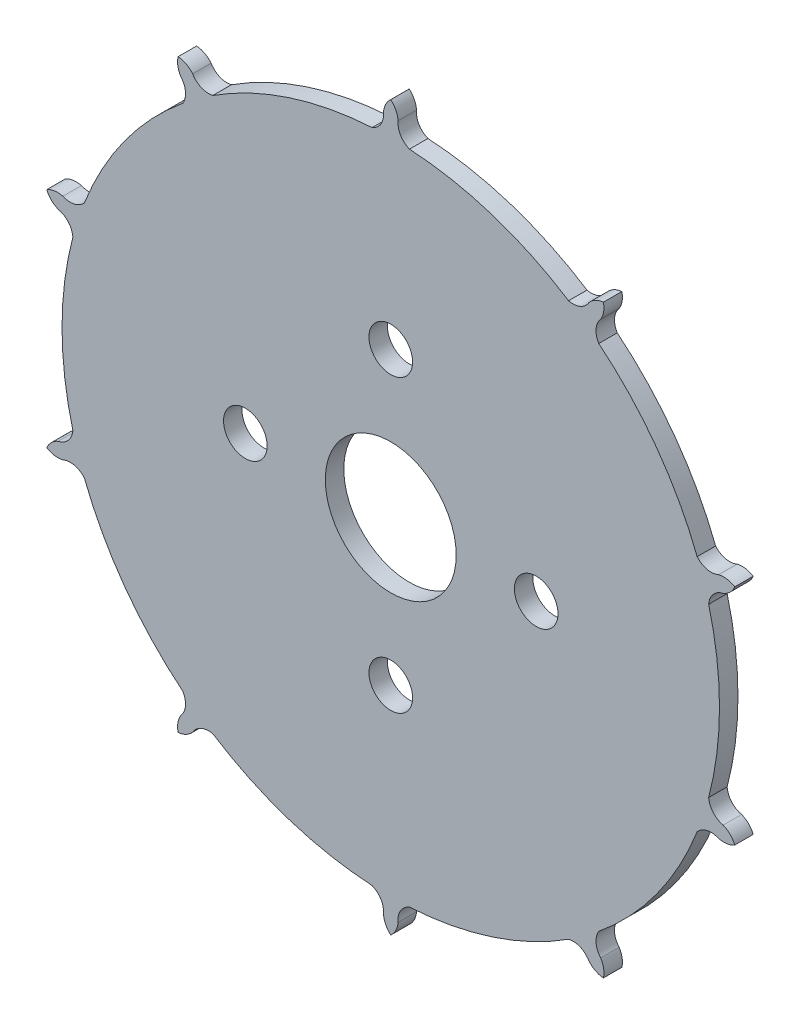
SolidWorks part; units mm, degrees
ref_plane "Front Plane" through (0, 0, 0) normal (0, 0, 1) x (1, 0, 0)
ref_plane "Top Plane" through (0, 0, 0) normal (0, 1, 0) x (1, 0, 0)
ref_plane "Right Plane" through (0, 0, 0) normal (1, 0, 0) x (0, 0, -1)
sketch "Sketch1" plane through (0, 0, 0) normal (0, 0, 1) x (1, 0, 0)
  circle A0 centre (0, 10) radius 1.5
  circle A1 centre (0, 0) radius 22.6042
  circle A6 centre (0, 0) radius 4.5
  circle A7 centre (10, 0) radius 1.5
  circle A8 centre (0, -10) radius 1.5
  circle A9 centre (-10, 0) radius 1.5
  dimension "D1" = 4
extrude "Boss-Extrude2" add sketch "Sketch1" along normal blind 1.27
sketch "Sketch2" plane through (0, 0, 1.27) normal (0, 0, 1) x (1, 0, 0)
  arc A0 (0, 24.8732) -> (-0.5, 23.868) centre (0.9512, 23.7732) ccw
  arc A1 (0, 24.8732) -> (0.5, 23.868) centre (-0.9512, 23.7732) cw
  arc A2 (-0.5, 23.868) -> (-1.6391, 22.4794) centre (-1.7638, 23.7433) cw
  arc A3 (0.5, 23.868) -> (1.6391, 22.4794) centre (1.7638, 23.7433) ccw
  arc A4 (-1.6391, 22.4794) -> (1.6391, 22.4794) centre (0, 31.849) ccw
extrude "Boss-Extrude4" add sketch "Sketch2" against normal blind 1.27
pattern_circular "CirPattern1" count 10 every 36 about axis through (0, 0, 0) along (0, 0, 1) of "Boss-Extrude4"
